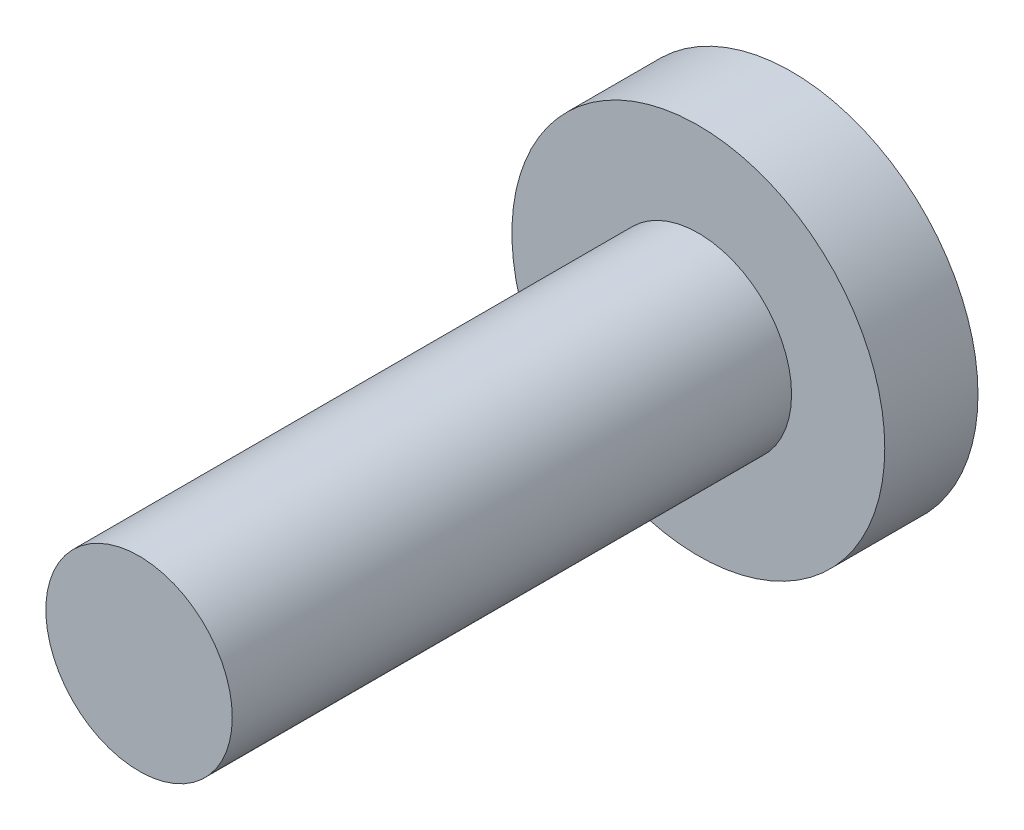
SolidWorks part; units mm, degrees
ref_plane "Plano frontal" through (0, 0, 0) normal (0, 0, 1) x (1, 0, 0)
ref_plane "Plano superior" through (0, 0, 0) normal (0, 1, 0) x (1, 0, 0)
ref_plane "Plano direito" through (0, 0, 0) normal (1, 0, 0) x (0, 0, -1)
sketch "Esboço1" plane through (0, 0, 0) normal (0, 0, 1) x (1, 0, 0)
  circle A0 centre (0, 0) radius 10
  dimension "D1" = 20
extrude "Ressalto-extrusão1" add sketch "Esboço1" along normal blind 5
sketch "Esboço2" plane through (0, 0, 5) normal (0, 0, 1) x (1, 0, 0)
  circle A0 centre (0, 0) radius 5
  dimension "D1" = 10
extrude "Ressalto-extrusão2" add sketch "Esboço2" along normal blind 30
